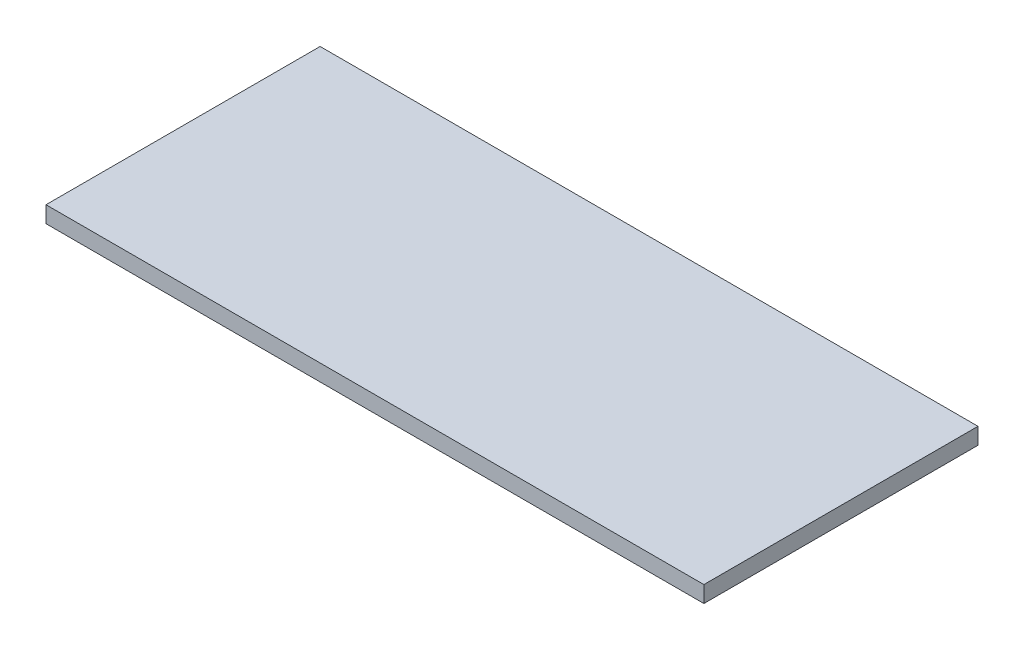
SolidWorks part; units mm, degrees
ref_plane "Front" through (0, 0, 0) normal (0, 0, 1) x (1, 0, 0)
ref_plane "Top" through (0, 0, 0) normal (0, 1, 0) x (1, 0, 0)
ref_plane "Right" through (0, 0, 0) normal (1, 0, 0) x (0, 0, -1)
sketch "Sketch1" plane through (0, 0, 0) normal (0, 1, 0) x (1, 0, 0)
  line L1 (0, 0) -> (120, 0)
  line L2 (0, 0) -> (0, 50)
  line L3 (0, 50) -> (120, 50)
  line L4 (120, 0) -> (120, 50)
  dimension "D1" = 120
  dimension "D2" = 50
extrude "Boss-Extrude1" add sketch "Sketch1" along normal blind 3
